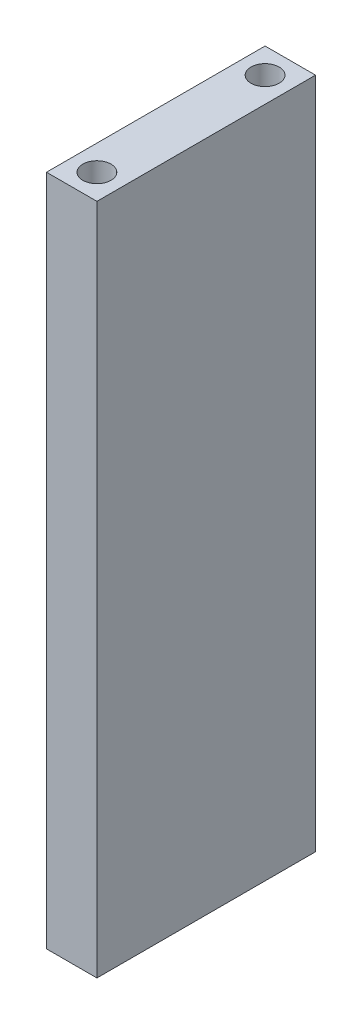
SolidWorks part; units mm, degrees
material "Custom Plastic"
ref_plane "X-Y Datum" through (0, 0, 0) normal (0, 0, 1) x (1, 0, 0)
ref_plane "X-Z Datum" through (0, 0, 0) normal (0, 1, 0) x (1, 0, 0)
ref_plane "Y-Z Datum" through (0, 0, 0) normal (1, 0, 0) x (0, 0, -1)
sketch "Sketch1" plane through (0, 0, 0) normal (0, 1, 0) x (1, 0, 0)
  line L0 (-142.0383, -6.5875) -> (-142.0383, -31.9875) construction
  line L2 (-145.8483, -35.7975) -> (-138.2283, -35.7975)
  line L3 (-145.8483, -35.7975) -> (-145.8483, -2.7775)
  line L4 (-145.8483, -2.7775) -> (-138.2283, -2.7775)
  line L5 (-138.2283, -35.7975) -> (-138.2283, -2.7775)
  line L6 (-145.8483, -35.7975) -> (-138.2283, -2.7775) construction
  line L7 (-145.8483, -2.7775) -> (-138.2283, -35.7975) construction
  circle A0 centre (-142.0383, -6.5875) radius 2.1273
  circle A1 centre (-142.0383, -31.9875) radius 2.1273
  point P0 (-142.0383, -6.5875)
  point P1 (-142.0383, -6.5875)
  point P4 (-142.0383, -19.2875)
  point P15 (-142.0383, -31.9875)
  dimension "D3" = 4.2545
  dimension "D1" = 33.02
  dimension "D2" = 7.62
extrude "Boss-Extrude1" add sketch "Sketch1" along normal mid plane 101.6
